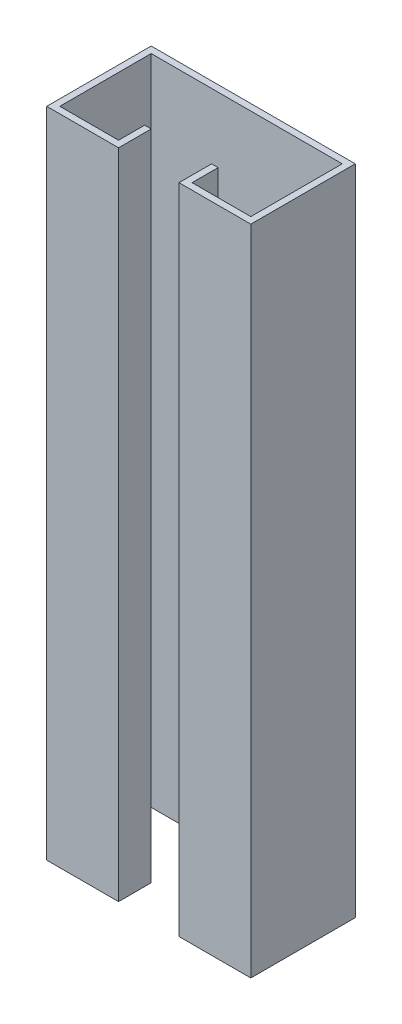
SolidWorks part; units mm, degrees
ref_plane "Front Plane" through (0, 0, 0) normal (0, 0, 1) x (1, 0, 0)
ref_plane "Top Plane" through (0, 0, 0) normal (0, 1, 0) x (1, 0, 0)
ref_plane "Right Plane" through (0, 0, 0) normal (1, 0, 0) x (0, 0, -1)
sketch "Sketch1" plane through (0, 0, 0) normal (0, 1, 0) x (1, 0, 0)
  line L0 (58.784, -12.7) -> (58.784, 50.8)
  line L1 (185.784, 177.8) -> (-185.784, 177.8)
  line L2 (-185.784, 177.8) -> (-185.784, 0)
  line L3 (-185.784, 0) -> (-71.484, 0)
  line L4 (-71.484, 0) -> (-71.484, 50.8)
  line L5 (71.484, 0) -> (71.484, 50.8)
  line L6 (185.784, 0) -> (71.484, 0)
  line L7 (185.784, 177.8) -> (185.784, 0)
  line L8 (198.484, -12.7) -> (58.784, -12.7)
  line L9 (198.484, 190.5) -> (198.484, -12.7)
  line L10 (198.484, 190.5) -> (-198.484, 190.5)
  line L11 (-198.484, 190.5) -> (-198.484, -12.7)
  line L12 (-198.484, -12.7) -> (-58.784, -12.7)
  line L13 (-58.784, -12.7) -> (-58.784, 50.8)
  line L14 (-71.484, 50.8) -> (-58.784, 50.8)
  line L15 (58.784, 50.8) -> (71.484, 50.8)
  dimension "D1" = 50.8
  dimension "D2" = 114.3
  dimension "D3" = 177.8
  dimension "D4" = 12.7
extrude "Boss-Extrude1" add sketch "Sketch1" along normal blind 1270
